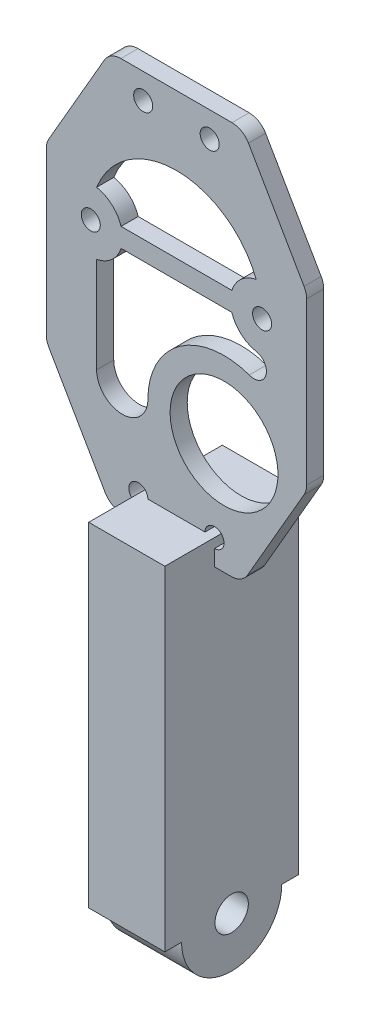
SolidWorks part; units mm, degrees
ref_plane "Front Plane" through (0, 0, 0) normal (0, 0, 1) x (1, 0, 0)
ref_plane "Top Plane" through (0, 0, 0) normal (0, 1, 0) x (1, 0, 0)
ref_plane "Right Plane" through (0, 0, 0) normal (1, 0, 0) x (0, 0, -1)
sketch "Sketch1" plane through (0, 0, 0) normal (0, 0, 1) x (1, 0, 0)
  line L0 (0, 34.1829) -> (0, -31) construction
  line L1 (-10.4877, 31) -> (10.4877, 31)
  line L2 (10.4877, 31) -> (20.1081, 14.337)
  line L3 (20.51, 12.837) -> (20.51, -12.5962)
  line L4 (20.1081, -14.0962) -> (10.3486, -31)
  line L5 (10.3486, -31) -> (-10.3486, -31)
  line L6 (-10.3486, -31) -> (-20.1081, -14.0962)
  line L7 (-20.51, -12.5962) -> (-20.51, 12.837)
  line L8 (-20.1081, 14.337) -> (-10.4877, 31)
  line L9 (-28.5813, 0) -> (26.9329, 0) construction
  line L10 (-12.58, -13.4) -> (-12.58, 1.6854)
  line L11 (-8.7303, 5.1) -> (8.7299, 5.1)
  line L12 (-8.7303, 8.1) -> (8.7299, 8.1)
  circle A0 centre (-5.24, 27) radius 1.5
  circle A1 centre (5.24, 27) radius 1.5
  circle A2 centre (-6, -27) radius 1.5
  circle A3 centre (6, -27) radius 1.5
  circle A4 centre (-13.5, 6.6) radius 1.5
  circle A5 centre (13.5, 6.6) radius 1.5
  circle A6 centre (7.5, -13.4) radius 8.5
  arc A7 (11.6226, -2.1304) -> (-4.5, -13.4) centre (7.5, -13.4) ccw
  arc A8 (11.4699, -2.0757) -> (12.5746, 1.686) centre (12.21, -0.25) ccw
  arc A9 (-12.58, -13.4) -> (-4.5, -13.4) centre (-8.54, -13.4) ccw
  arc A10 (-12.58, 1.6854) -> (-8.7303, 5.1) centre (-13.5, 6.6) ccw
  arc A11 (12.5739, 11.5139) -> (8.7299, 8.1) centre (13.5, 6.6) ccw
  arc A13 (12.5739, 11.5139) -> (-12.5741, 11.5135) centre (0, 6.6) ccw
  arc A14 (8.7299, 5.1) -> (12.5746, 1.686) centre (13.5, 6.6) ccw
  arc A15 (-8.7303, 8.1) -> (-12.5741, 11.5135) centre (-13.5, 6.6) ccw
  arc A16 (-20.1081, -14.0962) -> (-20.51, -12.5962) centre (-17.51, -12.5962) cw
  arc A17 (20.51, -12.5962) -> (20.1081, -14.0962) centre (17.51, -12.5962) cw
  arc A18 (20.1081, 14.337) -> (20.51, 12.837) centre (17.51, 12.837) cw
  arc A19 (-20.51, 12.837) -> (-20.1081, 14.337) centre (-17.51, 12.837) cw
  point P31 (0, 31)
  point P50 (20.51, -13.4)
  point P53 (20.51, 13.6408)
  point P56 (-20.51, 13.6408)
  dimension "D4" = 3
  dimension "D8" = 20.4
  dimension "D9" = 27
  dimension "D10" = 7.93
  dimension "D13" = 17
  dimension "D14" = 24
  dimension "D17" = 3.94
  dimension "D23" = 8.08
  dimension "D24" = 10
  dimension "D25" = 1.5
  dimension "D22" = 3
  dimension "D2" = 31
  dimension "D3" = 10.48
  dimension "D5" = 4
  dimension "D6" = 12
  dimension "D7" = 4
  dimension "D11" = 7.5
  dimension "D12" = 17.6
  dimension "D15" = 13.15
  dimension "D16" = 4.71
  dimension "D18" = 120
  dimension "D19" = 120
  dimension "D20" = 120
  dimension "D21" = 62
  dimension "D26" = 1.5
extrude "Boss-Extrude1" add sketch "Sketch1" along normal blind 2.7 contours A19 L7 A16 L6 L5 L4 A17 L3 A18 L2 L1 L8 A6 A5 A4 A3 A2 A1 A0 L11 A14 A8 A7 A9 L10 A10 L12 A15 A13 A11
fillet "Fillet1" radius 3 4 edges at (-10.3486, -31, 1.35) (10.3486, -31, 1.35) (10.4877, 31, 1.35) (-10.4877, 31, 1.35)
scale "Scale1" scale about centroid uniform scaling yes scale factor 1.9
sketch "Sketch2" plane through (0, 0, 3.915) normal (0, 0, 1) x (1, 0, 0)
  line L1 (-10.9592, -51.9654) -> (11.8408, -51.9654)
  line L2 (-10.9592, -51.9654) -> (-10.9592, -151.9654)
  line L3 (-10.9592, -151.9654) -> (11.8408, -151.9654)
  line L4 (11.8408, -51.9654) -> (11.8408, -151.9654)
  circle A0 centre (11.8408, -51.9654) radius 2.85 construction
  dimension "D1" = 100
extrude "Boss-Extrude2" add sketch "Sketch2" along normal mid plane 40 from vertex at -5.13 starting at point (-20.867, -56.7154, -1.215)
sketch "Sketch3" plane through (-10.9592, 0, 0) normal (-1, 0, 0) x (0, 0, 1)
  line L0 (18.785, -151.9654) -> (-21.215, -151.9654) construction
  circle A0 centre (-1.215, -151.9654) radius 15
  dimension "D1" = 30
extrude "Boss-Extrude3" add sketch "Sketch3" against normal up to surface (22.8 mm away) up to face at (11.8408, -57.1904, 1.35)
sketch "Sketch4" plane through (11.8408, 0, 0) normal (1, 0, 0) x (0, 0, -1)
  circle A0 centre (1.215, -151.9654) radius 5
  dimension "D1" = 10
extrude "Cut-Extrude1" cut sketch "Sketch4" against normal up to body separate body
